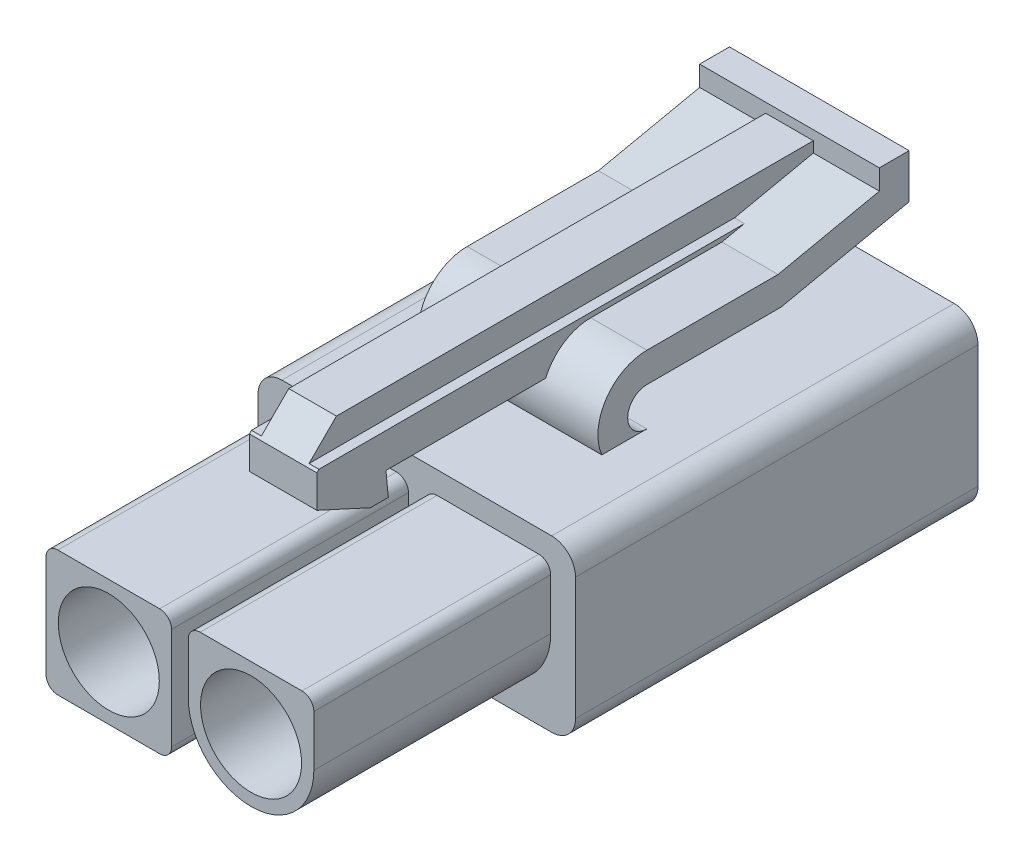
SolidWorks part; units mm, degrees
ref_plane "Front Plane" through (0, 0, 0) normal (0, 0, 1) x (1, 0, 0)
ref_plane "Top Plane" through (0, 0, 0) normal (0, 1, 0) x (1, 0, 0)
ref_plane "Right Plane" through (0, 0, 0) normal (1, 0, 0) x (0, 0, -1)
sketch "Sketch1" plane through (0, 0, 0) normal (0, 0, 1) x (1, 0, 0)
  line L1 (-6.66, -3.57) -> (6.66, -3.57)
  line L2 (-6.66, -3.57) -> (-6.66, 3.57)
  line L3 (-6.66, 3.57) -> (6.66, 3.57)
  line L4 (6.66, -3.57) -> (6.66, 3.57)
  line L5 (-6.66, -3.57) -> (6.66, 3.57) construction
  line L6 (-6.66, 3.57) -> (6.66, -3.57) construction
  point P0 (0, 0)
  dimension "D1" = 7.14
  dimension "D2" = 13.32
extrude "Boss-Extrude1" add sketch "Sketch1" against normal blind 16.89
sketch "Sketch2" plane through (0, 0, 0) normal (0, 0, 1) x (1, 0, 0)
  line L0 (0.35, 2.635) -> (0.35, 0)
  line L1 (-5.62, -2.635) -> (-0.35, -2.635)
  line L2 (-5.62, -2.635) -> (-5.62, 2.635)
  line L3 (-5.62, 2.635) -> (-0.35, 2.635)
  line L4 (-0.35, -2.635) -> (-0.35, 2.635)
  line L5 (-5.62, -2.635) -> (-0.35, 2.635) construction
  line L6 (-5.62, 2.635) -> (-0.35, -2.635) construction
  line L7 (5.62, 0) -> (5.62, 2.635)
  line L8 (5.62, 2.635) -> (0.35, 2.635)
  line L9 (-2.985, 0) -> (2.985, 0) construction
  arc A0 (0.35, 0) -> (5.62, 0) centre (2.985, 0) ccw
  point P0 (-2.985, 0)
  dimension "D1" = 5.27
  dimension "D2" = 11.24
extrude "Boss-Extrude2" add sketch "Sketch2" along normal offset from surface (9.94 mm away) 26.83
sketch "Sketch3" plane through (0, 0, 0) normal (0, 0, 1) x (1, 0, 0)
  line L0 (2.985, 0) -> (-2.985, 0) construction
  circle A0 centre (2.985, 0) radius 2.12
  circle A1 centre (-2.985, 0) radius 2.12
  dimension "D1" = 4.24
extrude "Cut-Extrude1" cut sketch "Sketch3" against normal through all both and the other way through all
sketch "Sketch4" plane through (0, 0, 0) normal (1, 0, 0) x (0, 0, -1)
  line L0 (5.885, 5.18) -> (11.5212, 5.18)
  line L1 (11.5212, 5.18) -> (16.89, 6.32)
  line L2 (16.89, 6.32) -> (16.89, 8.18)
  line L3 (16.89, 8.18) -> (15.64, 8.18)
  line L4 (15.64, 8.18) -> (15.64, 7.3324)
  line L5 (15.64, 7.3324) -> (11.39, 6.43)
  line L6 (11.39, 6.43) -> (5.885, 6.43)
  line L7 (16.89, 3.57) -> (0, 3.57) construction
  line L8 (3.9942, 3.57) -> (5.885, 3.57)
  line L9 (16.89, -3.57) -> (0, -3.57) construction
  line L10 (3.83, 4.375) -> (16.89, 4.375) construction
  line L11 (16.89, 4.375) -> (16.89, 6.32) construction
  line L12 (7.1795, 6.43) -> (7.1795, 5.18) construction
  line L13 (12.2207, 6.6064) -> (12.4803, 5.3837) construction
  line L14 (16.89, -3.57) -> (16.89, 3.57) construction
  arc A0 (5.885, 6.43) -> (3.9942, 3.57) centre (5.885, 4.375) ccw
  arc A1 (5.885, 5.18) -> (5.885, 3.57) centre (5.885, 4.375) ccw
  dimension "D1" = 1.25
  dimension "D2" = 10
  dimension "D3" = 13.06
  dimension "D4" = 11.75
  dimension "D5" = 2.75
  dimension "D6" = 5.5
extrude "Boss-Extrude3" add sketch "Sketch4" along normal mid plane 7.54
sketch "Sketch5" plane through (0, 0, 0) normal (1, 0, 0) x (0, 0, -1)
  line L0 (15.64, 7.78) -> (-4.3726, 7.78)
  line L1 (15.64, 8.18) -> (15.64, 7.3324) construction
  line L2 (-4.3726, 7.78) -> (-5.61, 6.5426)
  line L3 (-5.61, 6.5426) -> (-5.61, 5.18)
  line L4 (-5.61, 5.18) -> (-3.36, 4.15)
  line L6 (-2.71, 5.18) -> (5.5032, 5.18)
  line L7 (5.5032, 5.18) -> (15.64, 7.3324)
  line L8 (15.64, 7.3324) -> (15.64, 7.78)
  line L9 (15.64, 7.3324) -> (11.39, 6.43) construction
  line L11 (5.885, 5.18) -> (11.5212, 5.18) construction
  line L12 (16.89, 6.32) -> (16.89, 8.18) construction
  line L13 (-3.36, 4.15) -> (-2.61, 4.15)
  line L14 (-2.61, 4.15) -> (-2.71, 5.18)
  dimension "D1" = 2.6
  dimension "D2" = 22.5
  dimension "D3" = 135
  dimension "D4" = 1.75
  dimension "D5" = 3.63
  dimension "D6" = 3
  dimension "D7" = 2.9
  dimension "D8" = 0.75
extrude "Boss-Extrude4" add sketch "Sketch5" along normal mid plane 2.83
sketch "Sketch7" plane through (-1.415, 0, 0) normal (-1, 0, 0) x (0, 0, 1)
  line L0 (4.3726, 7.78) -> (5.61, 6.5426) construction
  line L1 (-15.64, 7.78) -> (4.3726, 7.78) construction
  line L2 (-15.64, 7.3324) -> (-15.64, 7.78) construction
  line L3 (-11.39, 6.43) -> (-15.64, 7.3324) construction
  line L4 (4.3726, 7.78) -> (5.5226, 6.63)
  line L5 (-15.64, 7.78) -> (4.3726, 7.78)
  line L6 (-15.64, 7.3324) -> (-15.64, 7.78)
  line L7 (-12.3319, 6.63) -> (-15.64, 7.3324)
  line L8 (5.5226, 6.63) -> (-12.3319, 6.63)
  dimension "D1" = 1.45
extrude "Cut-Extrude3" cut sketch "Sketch7" against normal blind 0.415
sketch "Sketch8" plane through (1.415, 0, 0) normal (1, 0, 0) x (0, 0, -1)
  line L5 (-4.3726, 7.78) -> (-5.5226, 6.63)
  line L6 (-5.5226, 6.63) -> (12.3319, 6.63)
  line L7 (12.3319, 6.63) -> (15.64, 7.3324)
  line L8 (15.64, 7.3324) -> (15.64, 7.78)
  line L9 (15.64, 7.78) -> (-4.3726, 7.78)
  line L10 (-4.3726, 7.78) -> (-5.5226, 6.63)
  line L11 (-5.5226, 6.63) -> (12.3319, 6.63)
  line L12 (12.3319, 6.63) -> (15.64, 7.3324)
  line L13 (15.64, 7.3324) -> (15.64, 7.78)
  line L14 (15.64, 7.78) -> (-4.3726, 7.78)
  dimension "D1" = 0
extrude "Cut-Extrude4" cut sketch "Sketch8" against normal blind 0.415
fillet "Fillet1" radius 1
fillet "Fillet2" radius 0.5
